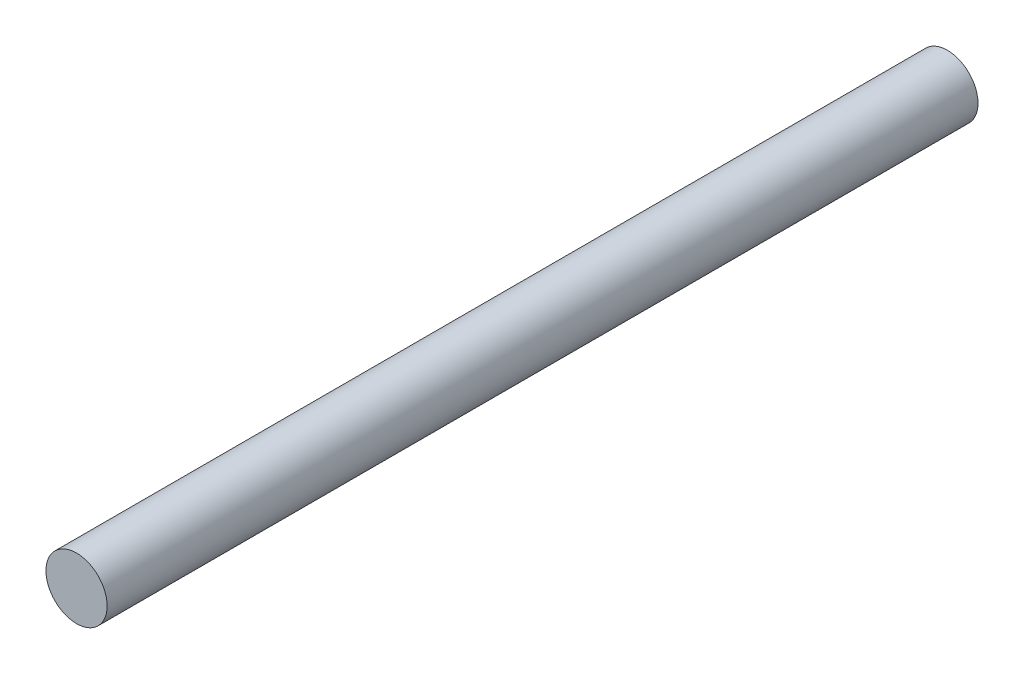
SolidWorks part; units mm, degrees
ref_plane "前视基准面" through (0, 0, 0) normal (0, 0, 1) x (1, 0, 0)
ref_plane "上视基准面" through (0, 0, 0) normal (0, 1, 0) x (1, 0, 0)
ref_plane "右视基准面" through (0, 0, 0) normal (1, 0, 0) x (0, 0, -1)
other "Configuration Table"
sketch "草图1" plane through (0, 0, 0) normal (0, 0, 1) x (1, 0, 0)
  circle A0 centre (0, 0) radius 2
  dimension "diameter" = 4
extrude "Cable_envelope" add sketch "草图1" along normal blind 56.92
